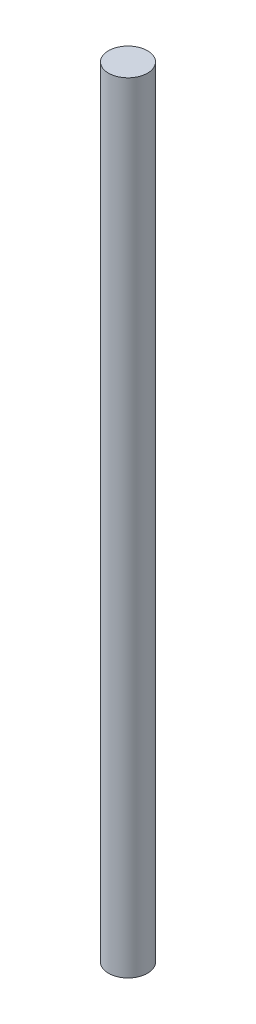
SolidWorks part; units mm, degrees
material "1060 合金"
ref_plane "前视基准面" through (0, 0, 0) normal (0, 0, 1) x (1, 0, 0)
ref_plane "上视基准面" through (0, 0, 0) normal (0, 1, 0) x (1, 0, 0)
ref_plane "右视基准面" through (0, 0, 0) normal (1, 0, 0) x (0, 0, -1)
other "Configuration Table"
sketch "草图1" plane through (0, 0, 0) normal (0, 1, 0) x (1, 0, 0)
  circle A0 centre (0, 0) radius 1
  dimension "D1" = 2
extrude "凸台-拉伸1" add sketch "草图1" along normal blind 40
